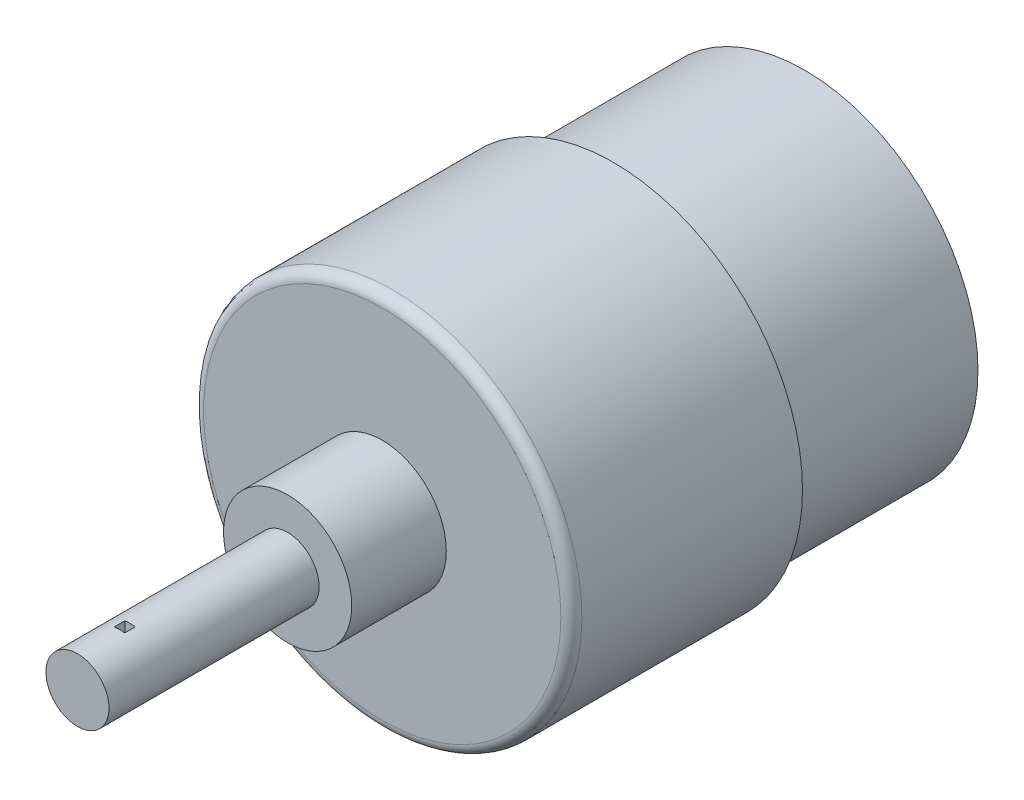
SolidWorks part; units mm, degrees
ref_plane "Front Plane" through (0, 0, 0) normal (0, 0, 1) x (1, 0, 0)
ref_plane "Top Plane" through (0, 0, 0) normal (0, 1, 0) x (1, 0, 0)
ref_plane "Right Plane" through (0, 0, 0) normal (1, 0, 0) x (0, 0, -1)
sketch "Sketch1" plane through (0, 0, 0) normal (0, 0, 1) x (1, 0, 0)
  circle A0 centre (0, 0) radius 18
  dimension "D1" = 36
extrude "Boss-Extrude1" add sketch "Sketch1" along normal blind 22
sketch "Sketch2" plane through (0, 0, 22) normal (0, 0, 1) x (1, 0, 0)
  circle A0 centre (0, 0) radius 6.1
  dimension "D1" = 12.2
extrude "Boss-Extrude2" add sketch "Sketch2" along normal blind 9
sketch "Sketch3" plane through (0, 0, 31) normal (0, 0, 1) x (1, 0, 0)
  circle A0 centre (0, 0) radius 3
  dimension "D1" = 6
extrude "Boss-Extrude3" add sketch "Sketch3" along normal blind 20
sketch "Sketch4" plane through (0, 0, 0) normal (0, 0, -1) x (-1, 0, 0)
  circle A0 centre (0, 0) radius 16.5
  dimension "D1" = 33
extrude "Boss-Extrude4" add sketch "Sketch4" along normal blind 18.2
fillet "Fillet1" radius 1 1 edges at (18, 0, 22)
sketch "Sketch5" plane through (0, 0, 51) normal (0, 0, 1) x (1, 0, 0)
  line L1 (-0.5, -4.8204) -> (0.5, -4.8204)
  line L2 (-0.5, -4.8204) -> (-0.5, 4.8204)
  line L3 (-0.5, 4.8204) -> (0.5, 4.8204)
  line L4 (0.5, -4.8204) -> (0.5, 4.8204)
  line L5 (-0.5, -4.8204) -> (0.5, 4.8204) construction
  line L6 (-0.5, 4.8204) -> (0.5, -4.8204) construction
  point P0 (0, 0)
  dimension "D1" = 1
extrude "Cut-Extrude1" cut sketch "Sketch5" against normal blind 1 from offset 4
